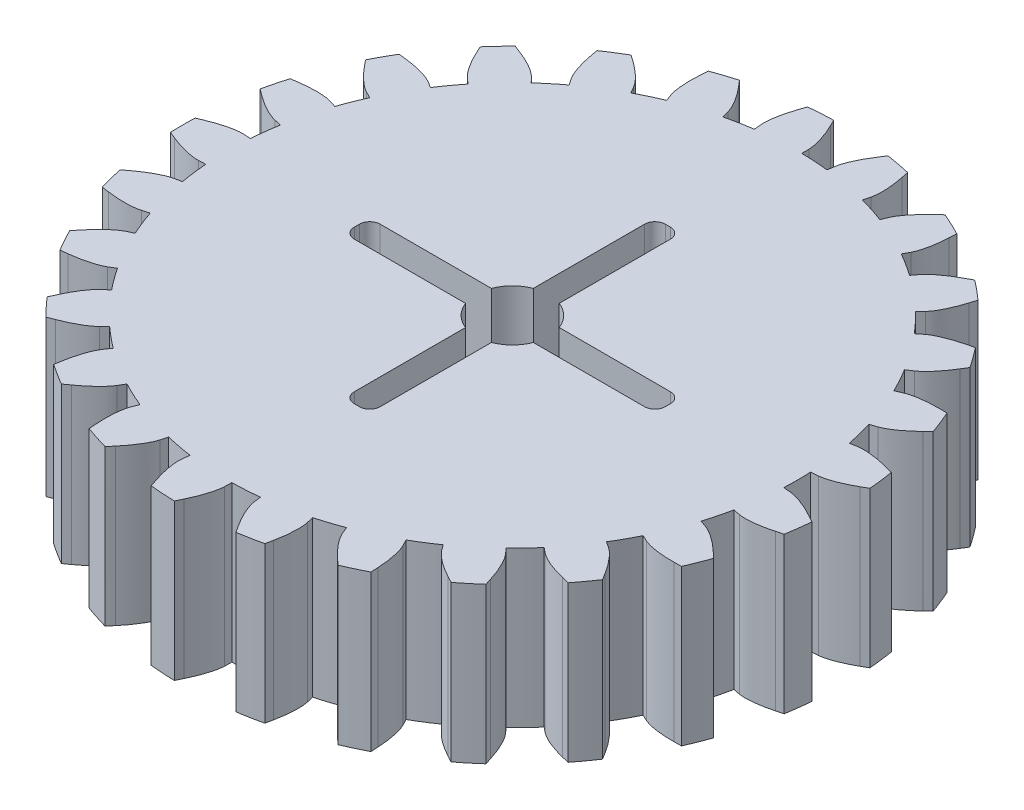
SolidWorks part; units mm, degrees
ref_plane "Front Plane" through (0, 0, 0) normal (0, 0, 1) x (1, 0, 0)
ref_plane "Top Plane" through (0, 0, 0) normal (0, 1, 0) x (1, 0, 0)
ref_plane "Right Plane" through (0, 0, 0) normal (1, 0, 0) x (0, 0, -1)
sketch "Sketch1" plane through (0, 0, 0) normal (0, 1, 0) x (1, 0, 0)
  line L0 (0, 30) -> (-129.8026, 30) construction
  line L1 (-99.777, -6.3159) -> (118.111, 72.9889) construction
  circle A0 centre (0, 0) radius 30
  circle A1 centre (0, 0) radius 28.1908
  dimension "D1" = 60
  dimension "D2" = 20
sketch "Sketch2" plane through (0, 0, 0) normal (0, 1, 0) x (1, 0, 0)
  line L0 (0, 0) -> (-9.6418, 26.4907) construction
  line L1 (-99.777, -6.3159) -> (118.111, 72.9889) construction
  line L2 (-9.6418, 26.4907) -> (0, 30)
  line L3 (-10.3543, 26.2204) -> (0, 0) construction
  line L4 (-10.3543, 26.2204) -> (-0.1021, 30.2689) construction
  line L5 (0, 0) -> (-11.0591, 25.931) construction
  line L6 (0, 0) -> (-11.7559, 25.6226) construction
  line L7 (-12.4441, 25.2955) -> (0, 0) construction
  line L8 (0, 0) -> (-13.1232, 24.95) construction
  line L9 (-8.9223, 26.7416) -> (0.088, 29.7479) construction
  line L10 (-11.0591, 25.931) -> (-0.2192, 30.554) construction
  line L11 (-11.7559, 25.6226) -> (-0.3523, 30.8547) construction
  line L12 (-12.4441, 25.2955) -> (-0.5023, 31.1703) construction
  line L13 (-6.7269, 27.3764) -> (0.2773, 29.0975) construction
  line L14 (-7.4643, 27.1846) -> (0.2256, 29.2961) construction
  line L15 (-5.9846, 27.5482) -> (0.319, 28.9176) construction
  line L16 (-8.1963, 26.973) -> (0.1629, 29.5131) construction
  line L17 (-5.2378, 27.6999) -> (0.3517, 28.7569) construction
  circle A0 centre (0, 0) radius 28.1908 construction
  arc A1 (-9.6418, 26.4907) -> (-10.3543, 26.2204) centre (0, 0) ccw
  arc A2 (-10.3543, 26.2204) -> (-11.0591, 25.931) centre (0, 0) ccw
  arc A3 (-11.0591, 25.931) -> (-11.7559, 25.6226) centre (0, 0) ccw
  arc A4 (-11.7559, 25.6226) -> (-12.4441, 25.2955) centre (0, 0) ccw
  arc A5 (-12.4441, 25.2955) -> (-13.1232, 24.95) centre (0, 0) ccw
  arc A6 (-9.6418, 26.4907) -> (-8.9223, 26.7416) centre (0, 0) cw
  arc A7 (-8.9223, 26.7416) -> (-8.1963, 26.973) centre (0, 0) cw
  arc A8 (-8.1963, 26.973) -> (-7.4643, 27.1846) centre (0, 0) cw
  arc A9 (-7.4643, 27.1846) -> (-6.7269, 27.3764) centre (0, 0) cw
  arc A10 (-6.7269, 27.3764) -> (-5.9846, 27.5482) centre (0, 0) cw
  arc A11 (-5.9846, 27.5482) -> (-5.2378, 27.6999) centre (0, 0) cw
  dimension "D1" = 10.2606
  dimension "D3" = 11.0226
  dimension "D8" = 11.7846
  dimension "D9" = 12.5466
  dimension "D10" = 13.3086
  dimension "D15" = 9.4986
  dimension "D16" = 8.7366
  dimension "D17" = 7.9746
  dimension "D18" = 7.2126
  dimension "D21" = 6.4506
  dimension "D22" = 5.6886
  dimension "D2" = 0.762
  dimension "D4" = 0.762
  dimension "D5" = 0.762
  dimension "D6" = 0.762
  dimension "D7" = 0.762
  dimension "D11" = 0.762
  dimension "D12" = 0.762
  dimension "D13" = 0.762
  dimension "D14" = 0.762
  dimension "D19" = 0.762
  dimension "D20" = 0.762
sketch "Sketch4" plane through (0, 0, 0) normal (0, 1, 0) x (1, 0, 0)
  line L0 (0, 0) -> (0, 39.7853) construction
  line L1 (0, 0) -> (-2.5084, 39.8703) construction
  circle A0 centre (0, 0) radius 28.1908 construction
  circle A1 centre (0, 0) radius 31.81
  circle A2 centre (0, 0) radius 30 construction
  spline S0 degree 3 poles (-0.5023, 31.1703) (-0.4025, 30.9674) (-0.2649, 30.6686) (-0.1033, 30.2758) (-0.0012, 30.0069) (0.0869, 29.7547) (0.1619, 29.52) (0.2247, 29.303) (0.2766, 29.1044) (0.3615, 28.7384) (0.4102, 28.4344) (0.4191, 28.1877) knots 0 0 0 0 0.215965 0.31411 0.405697 0.490726 0.569196 0.641109 0.706463 0.765259 1 1 1 1
  spline S1 degree 3 poles (-3.4083, 30.9875) (-3.4819, 30.7737) (-3.581, 30.46) (-3.692, 30.05) (-3.7597, 29.7704) (-3.8155, 29.5092) (-3.8604, 29.2669) (-3.8956, 29.0438) (-3.9221, 28.8402) (-3.9605, 28.4664) (-3.9707, 28.1588) (-3.9486, 27.9129) knots 0 0 0 0 0.215965 0.31411 0.405697 0.490726 0.569196 0.641109 0.706463 0.765259 1 1 1 1
  spline S2 degree 2 poles (-3.4083, 30.9875) (-3.2603, 31.434) (-3.1869, 31.65) knots 0 0 0 1 1 1
  spline S3 degree 2 poles (-0.5023, 31.1703) (-0.7051, 31.5947) (-0.805, 31.7998) knots 0 0 0 1 1 1
  dimension "D2" = 1.81
  dimension "D1" = 3.6
sketch "Sketch5" plane through (0, 0, 0) normal (0, 1, 0) x (1, 0, 0)
  circle A1 centre (0, 0) radius 27.5
  dimension "D1" = 55
extrude "Boss-Extrude1" add sketch "Sketch5" along normal blind 15
sketch "Sketch7" plane through (0, 0, 0) normal (0, 1, 0) x (1, 0, 0)
  line L0 (0.4191, 28.1877) -> (0.4191, 27.4968)
  circle A2 centre (0, 0) radius 27.5
  arc A3 (0.4191, 27.4968) -> (-3.8796, 27.225) centre (0, 0) ccw
  circle A5 centre (0, 0) radius 31.81
  arc A6 (-0.805, 31.7998) -> (-3.1869, 31.65) centre (0, 0) ccw
  spline S2 degree 2 poles (1274.8199, -2684.1688) (-1275.8104, 2748.1183) (1273.1943, -2684.1016) knots -109.339646 -109.339646 -109.339646 113.20807 113.20807 113.20807 only from (-0.5023, 31.1703) to (-0.805, 31.7998)
  spline S3 degree 2 poles (-0.5023, 31.1703) (-0.7051, 31.5947) (-0.805, 31.7998) knots 0 0 0 1 1 1
  spline S5 degree 3 poles (2998.75, -30.18) (-181.7072, 31.7269) (-13.9419, 63.9356) (-0.1033, 30.2758) (-0.0012, 30.0069) (0.0869, 29.7547) (0.1619, 29.52) (0.2247, 29.303) (0.2766, 29.1044) (3.4004, 15.6431) (-35.1593, -6.9752) (-2993.4136, -158.0668) knots -34.354648 -34.354648 -34.354648 -34.354648 0.215965 0.31411 0.405697 0.490726 0.569196 0.641109 0.706463 0.765259 13.840232 13.840232 13.840232 13.840232 only from (-0.5023, 31.1703) to (0.4191, 28.1877)
  spline S6 degree 3 poles (-0.5023, 31.1703) (-0.4025, 30.9674) (-0.2649, 30.6686) (-0.1033, 30.2758) (-0.0012, 30.0069) (0.0869, 29.7547) (0.1619, 29.52) (0.2247, 29.303) (0.2766, 29.1044) (0.3615, 28.7384) (0.4102, 28.4344) (0.4191, 28.1877) knots 0 0 0 0 0.215965 0.31411 0.405697 0.490726 0.569196 0.641109 0.706463 0.765259 1 1 1 1
  spline S8 degree 2 poles (-928.352, -2822.7807) (921.3197, 2886.35) (-926.7476, -2822.5102) knots -109.339646 -109.339646 -109.339646 113.20807 113.20807 113.20807 only from (-3.4083, 30.9875) to (-3.1869, 31.65)
  spline S9 degree 2 poles (-3.4083, 30.9875) (-3.2603, 31.434) (-3.1869, 31.65) knots 0 0 0 1 1 1
  spline S10 degree 1 poles (-3.9486, 27.9129) (-3.8796, 27.225) knots 0 0 1 1
  spline S11 degree 3 poles (-2971.3214, -405.785) (176.2979, 54.2507) (5.8187, 65.1788) (-3.692, 30.05) (-3.7597, 29.7704) (-3.8155, 29.5092) (-3.8604, 29.2669) (-3.8956, 29.0438) (-3.9221, 28.8402) (-5.3342, 15.0936) (35.7563, -2.5136) (2989.6206, 218.3538) knots -34.354648 -34.354648 -34.354648 -34.354648 0.215965 0.31411 0.405697 0.490726 0.569196 0.641109 0.706463 0.765259 13.840232 13.840232 13.840232 13.840232 only from (-3.4083, 30.9875) to (-3.9486, 27.9129)
  spline S12 degree 3 poles (-3.4083, 30.9875) (-3.4819, 30.7737) (-3.581, 30.46) (-3.692, 30.05) (-3.7597, 29.7704) (-3.8155, 29.5092) (-3.8604, 29.2669) (-3.8956, 29.0438) (-3.9221, 28.8402) (-3.9605, 28.4664) (-3.9707, 28.1588) (-3.9486, 27.9129) knots 0 0 0 0 0.215965 0.31411 0.405697 0.490726 0.569196 0.641109 0.706463 0.765259 1 1 1 1
  dimension "D1" = 0
  dimension "D2" = 0
  dimension "D3" = 0
  dimension "D4" = 0
  dimension "D5" = 0
  dimension "D6" = 0
extrude "Boss-Extrude2" add sketch "Sketch7" along normal blind 15
sketch "Sketch8" plane through (0, 0, 0) normal (1, 0, 0) x (0, 0, -1)
  line L0 (0, 0) -> (-0.0016, 15) construction
  line L1 (27.4968, 15) -> (-27.5, 15) construction
pattern_circular "CirPattern2" count 25 over 360 about axis through (0, 15, 0) along (0, 1, 0) of "Boss-Extrude2"
sketch "Sketch9" plane through (0, 15, 0) normal (0, 1, 0) x (1, 0, 0)
  line L0 (0, -20.6825) -> (0, 17.5955) construction
  line L1 (19.9592, 0) -> (-20.7001, 0) construction
  line L2 (1.25, 3.2692) -> (1.25, 15)
  line L3 (1.25, -15) -> (-1.25, -15)
  line L4 (1.25, -15) -> (1.25, -3.2692)
  line L5 (1.25, 15) -> (-1.25, 15)
  line L6 (-1.25, -15) -> (-1.25, -3.2692)
  line L7 (1.25, -15) -> (-1.25, 15) construction
  line L8 (1.25, 15) -> (-1.25, -15) construction
  line L9 (15, -1.25) -> (3.2692, -1.25)
  line L10 (15, -1.25) -> (15, 1.25)
  line L11 (15, 1.25) -> (3.2692, 1.25)
  line L12 (-15, -1.25) -> (-15, 1.25)
  line L13 (15, -1.25) -> (-15, 1.25) construction
  line L14 (15, 1.25) -> (-15, -1.25) construction
  line L15 (-1.25, 3.2692) -> (-1.25, 15)
  line L19 (-3.2692, -1.25) -> (-15, -1.25)
  line L21 (-3.2692, 1.25) -> (-15, 1.25)
  arc A1 (-1.25, 3.2692) -> (-3.2692, 1.25) centre (0, 0) ccw
  arc A3 (-3.2692, -1.25) -> (-1.25, -3.2692) centre (0, 0) ccw
  arc A4 (1.25, -3.2692) -> (3.2692, -1.25) centre (0, 0) ccw
  arc A5 (3.2692, 1.25) -> (1.25, 3.2692) centre (0, 0) ccw
  dimension "D2" = 2.5
  dimension "D3" = 30
extrude "Cut-Extrude1" cut sketch "Sketch9" against normal through all
fillet "Fillet1" radius 1 8 edges at (1.25, 7.5, -15) (15, 7.5, -1.25) (-1.25, 7.5, 15) (1.25, 7.5, 15) (15, 7.5, 1.25) (-15, 7.5, 1.25) (-15, 7.5, -1.25) (-1.25, 7.5, -15)
equation "\"D3@Sketch2\"=\"D1@Sketch2\"+\"D2@Sketch2\""
equation "\"D4@Sketch2\"=\"D2@Sketch2\""
equation "\"D5@Sketch2\"=\"D2@Sketch2\""
equation "\"D6@Sketch2\"=\"D2@Sketch2\""
equation "\"D7@Sketch2\"=\"D2@Sketch2\""
equation "\"D8@Sketch2\"=\"D3@Sketch2\"+\"D2@Sketch2\""
equation "\"D9@Sketch2\"=\"D8@Sketch2\"+\"D2@Sketch2\""
equation "\"D12@Sketch2\"=\"D11@Sketch2\""
equation "\"D13@Sketch2\"=\"D12@Sketch2\""
equation "\"D14@Sketch2\"=\"D12@Sketch2\""
equation "\"D15@Sketch2\"=\"D1@Sketch2\"-\"D11@Sketch2\""
equation "\"D16@Sketch2\"=\"D15@Sketch2\"-\"D11@Sketch2\""
equation "\"D17@Sketch2\"=\"D16@Sketch2\"-\"D11@Sketch2\""
equation "\"D18@Sketch2\"=\"D17@Sketch2\"-\"D11@Sketch2\""
equation "\"D10@Sketch2\"=\"D1@Sketch2\" + 4*\"D11@Sketch2\""
equation "\"D21@Sketch2\"=\"D18@Sketch2\"-\"D11@Sketch2\""
equation "\"D22@Sketch2\"=\"D21@Sketch2\"-\"D11@Sketch2\""
